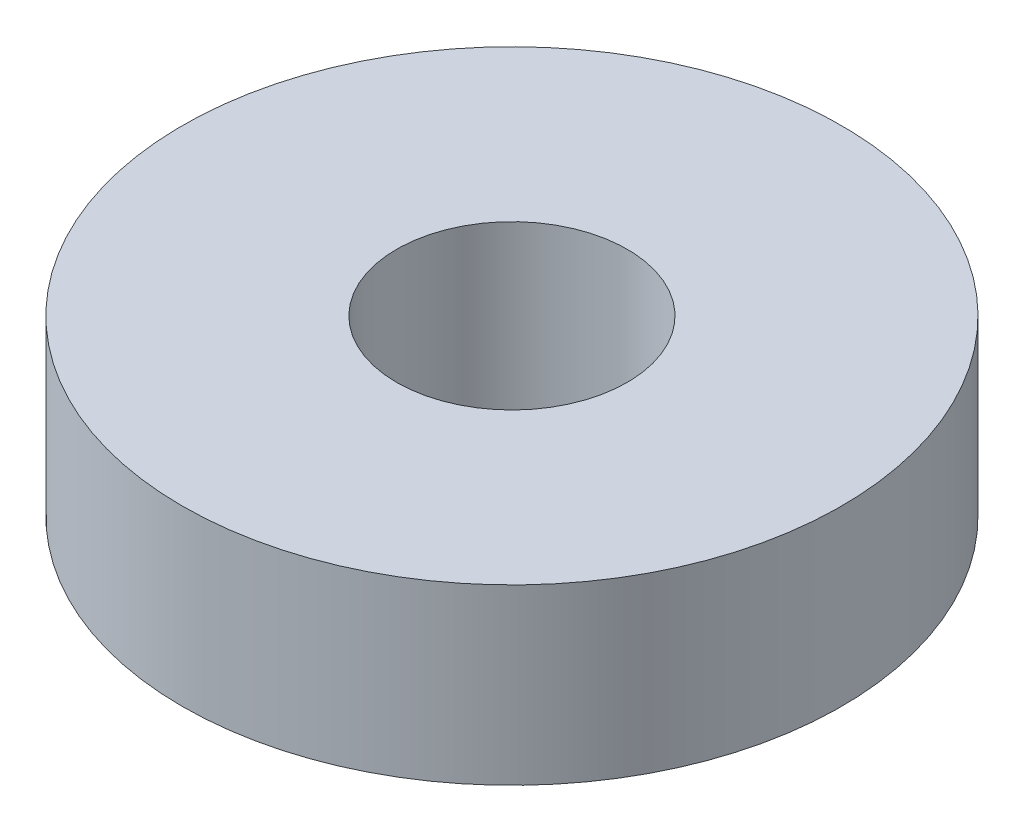
SolidWorks part; units mm, degrees
material "Plain Carbon Steel"
ref_plane "Front Plane" through (0, 0, 0) normal (0, 0, 1) x (1, 0, 0)
ref_plane "Top Plane" through (0, 0, 0) normal (0, 1, 0) x (1, 0, 0)
ref_plane "Right Plane" through (0, 0, 0) normal (1, 0, 0) x (0, 0, -1)
sketch "Sketch1" plane through (0, 0, 0) normal (0, 1, 0) x (1, 0, 0)
  circle A0 centre (0, 0) radius 7.62
  dimension "D1" = 15.24
extrude "Boss-Extrude1" add sketch "Sketch1" along normal blind 4.0132 contours A0
sketch "Sketch2" plane through (0, 4.0132, 0) normal (0, 1, 0) x (1, 0, 0)
  circle A0 centre (0, 0) radius 2.667
  dimension "D1" = 5.334
extrude "Cut-Extrude1" cut sketch "Sketch2" against normal blind 4.0132 contours A0
